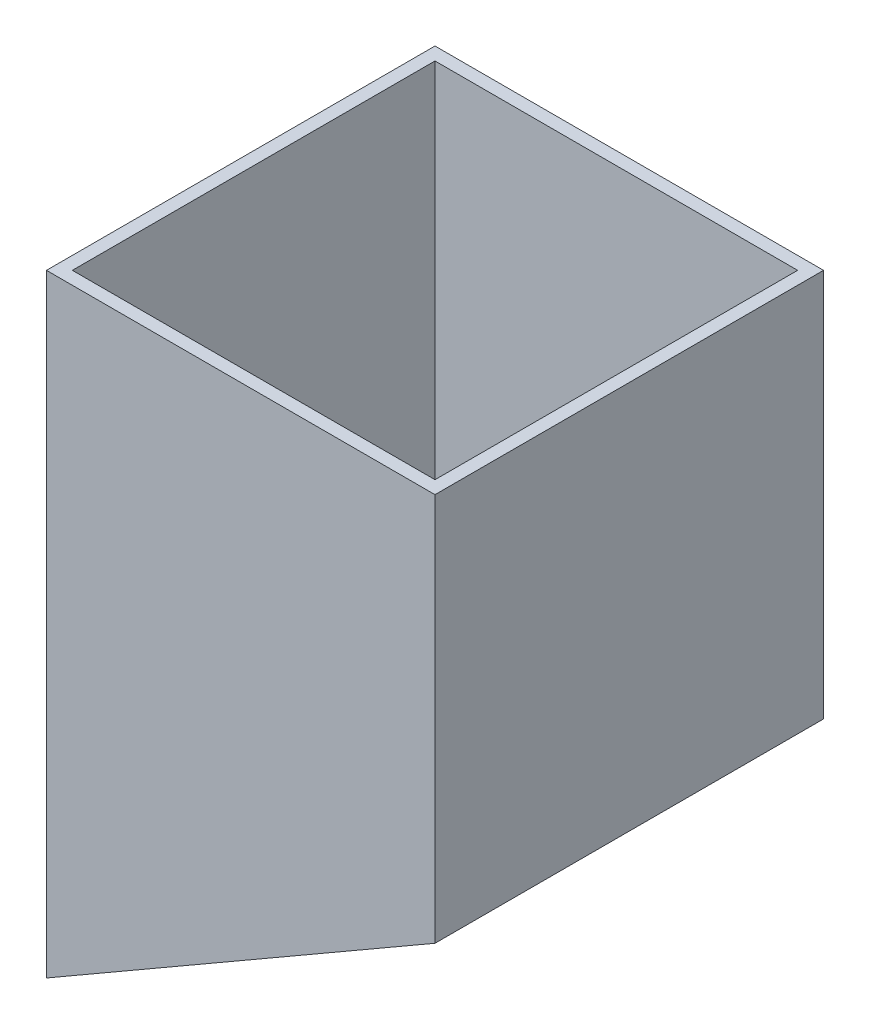
SolidWorks part; units mm, degrees
ref_plane "Alzado" through (0, 0, 0) normal (0, 0, 1) x (1, 0, 0)
ref_plane "Planta" through (0, 0, 0) normal (0, 1, 0) x (1, 0, 0)
ref_plane "Vista lateral" through (0, 0, 0) normal (1, 0, 0) x (0, 0, -1)
sketch "Croquis1" plane through (0, 0, 0) normal (0, 1, 0) x (1, 0, 0)
  line L1 (0, 0) -> (300, 0)
  line L2 (0, 0) -> (0, 300)
  line L3 (0, 300) -> (300, 300)
  line L4 (300, 0) -> (300, 300)
  dimension "D1" = 300
  dimension "D2" = 300
extrude "Saliente-Extruir1" add sketch "Croquis1" along normal blind 300
sketch "Croquis2" plane through (0, 0, 0) normal (0, 0, 1) x (1, 0, 0)
  line L0 (0, 0) -> (0, -173.2051)
  line L1 (0, -173.2051) -> (300, 0)
  line L2 (300, 0) -> (0, 0)
  dimension "D1" = 30
extrude "Saliente-Extruir2" add sketch "Croquis2" against normal up to surface (300 mm away) up to face at (150, 150, -300)
shell "Vaciado4" thickness 10
